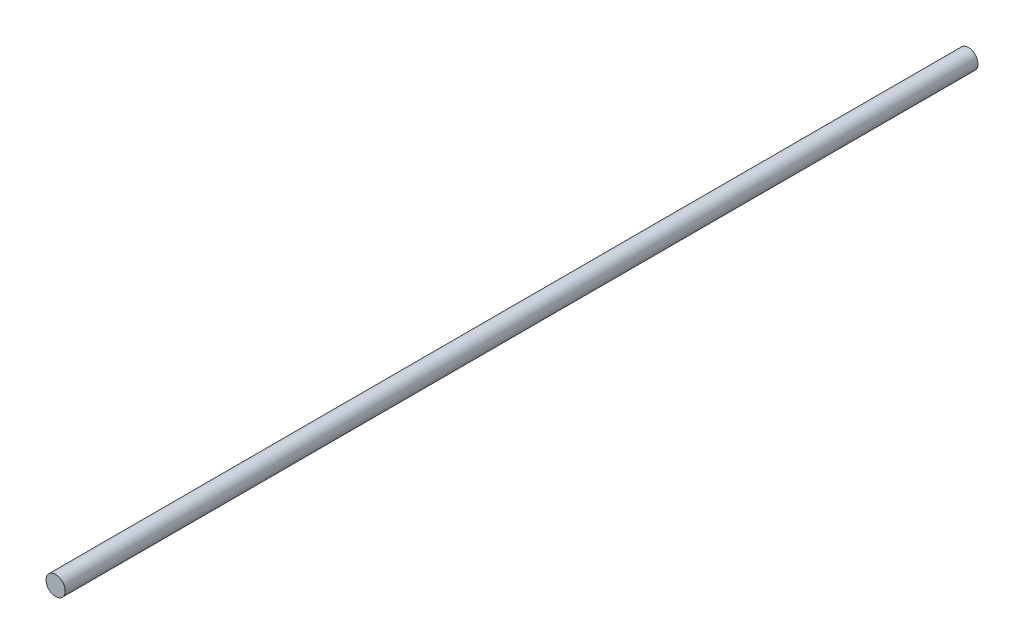
SolidWorks part; units mm, degrees
ref_plane "Front Plane" through (0, 0, 0) normal (0, 0, 1) x (1, 0, 0)
ref_plane "Top Plane" through (0, 0, 0) normal (0, 1, 0) x (1, 0, 0)
ref_plane "Right Plane" through (0, 0, 0) normal (1, 0, 0) x (0, 0, -1)
sketch "Sketch1" plane through (0, 0, 0) normal (0, 0, 1) x (1, 0, 0)
  circle A0 centre (0, 0) radius 4
  dimension "D1" = 8
extrude "Boss-Extrude1" add sketch "Sketch1" along normal blind 380
